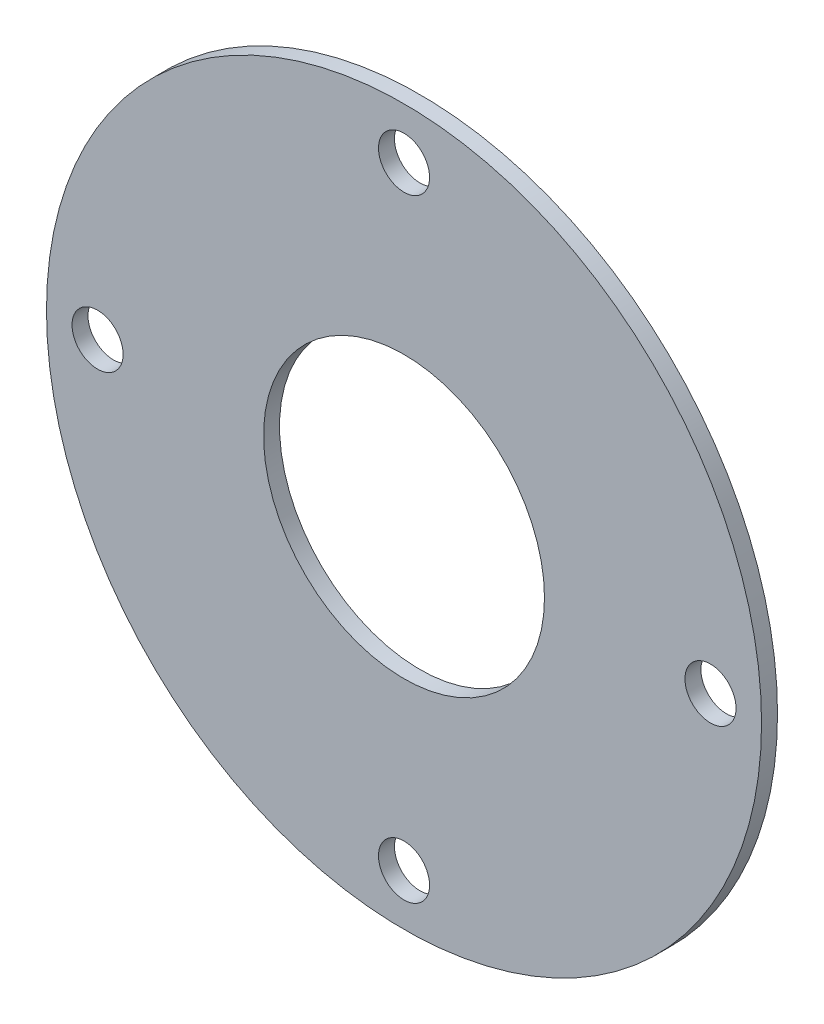
SolidWorks part; units mm, degrees
ref_plane "Спереди" through (0, 0, 0) normal (0, 0, 1) x (1, 0, 0)
ref_plane "Сверху" through (0, 0, 0) normal (0, 1, 0) x (1, 0, 0)
ref_plane "Справа" through (0, 0, 0) normal (1, 0, 0) x (0, 0, -1)
sketch "Эскиз1" plane through (0, 0, 0) normal (0, 0, 1) x (1, 0, 0)
  circle A0 centre (0, 0) radius 56
  circle A1 centre (0, 0) radius 22
extrude "Carrier_rear" add sketch "Эскиз1" along normal blind 2.5 from offset 32
sketch "Эскиз2" plane through (0, 0, 0) normal (0, 0, 1) x (1, 0, 0)
  circle A0 centre (48, 0) radius 4
  circle A1 centre (0, 48) radius 4
  circle A2 centre (-48, 0) radius 4
  circle A3 centre (0, -48) radius 4
extrude "Through_holes" cut sketch "Эскиз2" against normal mid plane 200
